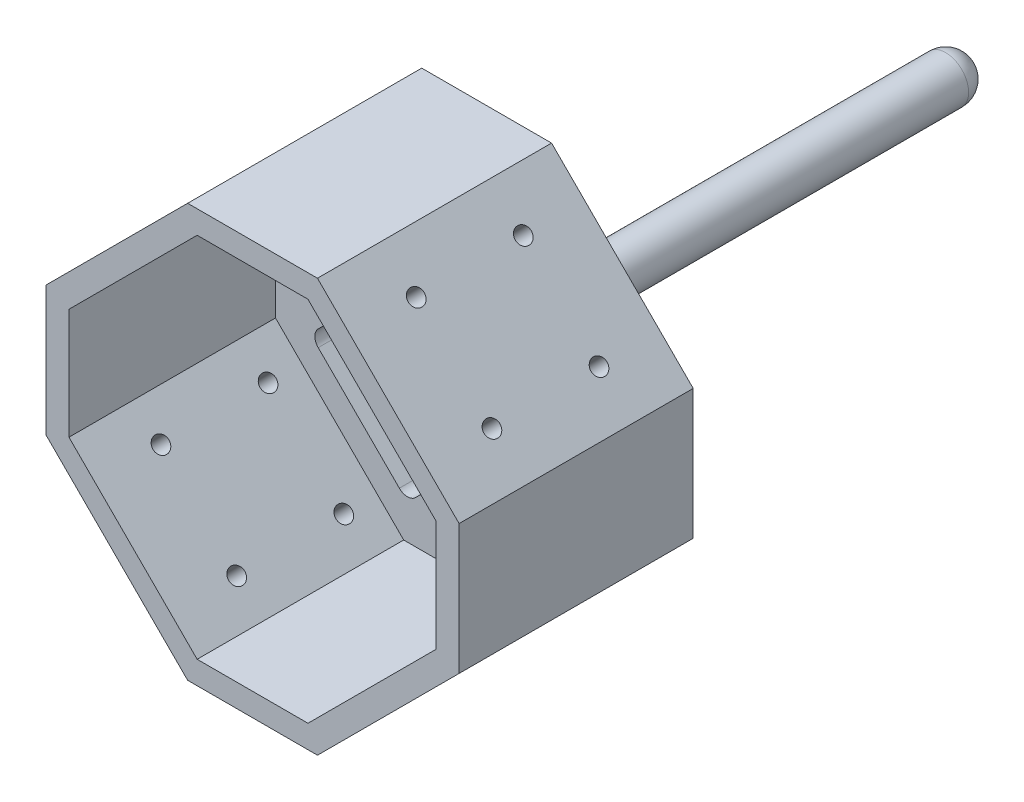
SolidWorks part; units mm, degrees
ref_plane "Plan de face" through (0, 0, 0) normal (0, 0, 1) x (1, 0, 0)
ref_plane "Plan de dessus" through (0, 0, 0) normal (0, 1, 0) x (1, 0, 0)
ref_plane "Plan de droite" through (0, 0, 0) normal (1, 0, 0) x (0, 0, -1)
sketch "Esquisse4" plane through (0, 0, 0) normal (0, 0, 1) x (1, 0, 0)
  line L1 (-14.1421, 45) -> (14.1421, 45)
  line L2 (-45, 14.1421) -> (-45, -14.1421)
  line L3 (-14.1421, -45) -> (14.1421, -45)
  line L4 (45, 14.1421) -> (45, -14.1421)
  line L5 (-45, 14.1421) -> (-14.1421, 45)
  line L6 (14.1421, 45) -> (45, 14.1421)
  line L10 (45, -14.1421) -> (14.1421, -45)
  line L11 (-14.1421, -45) -> (-45, -14.1421)
  point P0 (0, 0)
  point P10 (-59.1421, 0)
  point P11 (0, 59.1421)
  point P12 (59.1421, 0)
  point P13 (0, -59.1421)
extrude "Boss.-Extru.2" add sketch "Esquisse4" along normal blind 50
sketch "Esquisse5" plane through (29.5711, 29.5711, 0) normal (0.7071, 0.7071, 0) x (0, 0, -1)
  circle A0 centre (-13.335, 11.665) radius 1.75
  circle A1 centre (-36.665, 11.665) radius 1.75
  circle A2 centre (-13.335, -11.665) radius 1.75
  circle A3 centre (-36.665, -11.665) radius 1.75
  point P5 (-25, 0)
  dimension "D3" = 3.5
  dimension "D1" = 23.33
  dimension "D2" = 23.33
extrude "Enlèv. mat.-Extru.2" cut sketch "Esquisse5" against normal through all
sketch "Esquisse6" plane through (29.5711, -29.5711, 0) normal (0.7071, -0.7071, 0) x (0, 0, -1)
  circle A0 centre (-13.335, 11.665) radius 1.75
  circle A1 centre (-36.665, 11.665) radius 1.75
  circle A2 centre (-13.335, -11.665) radius 1.75
  circle A3 centre (-36.665, -11.665) radius 1.75
  point P5 (-25, 0)
  dimension "D3" = 3.5
  dimension "D1" = 23.33
  dimension "D2" = 23.33
extrude "Enlèv. mat.-Extru.3" cut sketch "Esquisse6" against normal through all
sketch "Esquisse7" plane through (0, 0, 50) normal (0, 0, 1) x (1, 0, 0)
  line L0 (-45, 14.1421) -> (-14.1421, 45)
  line L1 (-14.1421, 45) -> (14.1421, 45)
  line L2 (14.1421, 45) -> (45, 14.1421)
  line L3 (45, 14.1421) -> (45, -14.1421)
  line L4 (45, -14.1421) -> (14.1421, -45)
  line L5 (14.1421, -45) -> (-14.1421, -45)
  line L6 (-14.1421, -45) -> (-45, -14.1421)
  line L7 (-45, -14.1421) -> (-45, 14.1421)
  line L8 (-40, 12.0711) -> (-12.0711, 40)
  line L9 (-12.0711, 40) -> (12.0711, 40)
  line L10 (12.0711, 40) -> (40, 12.0711)
  line L11 (40, 12.0711) -> (40, -12.0711)
  line L12 (40, -12.0711) -> (12.0711, -40)
  line L13 (12.0711, -40) -> (-12.0711, -40)
  line L14 (-12.0711, -40) -> (-40, -12.0711)
  line L15 (-40, -12.0711) -> (-40, 12.0711)
  dimension "D1" = 5
extrude "Enlèv. mat.-Extru.5" cut sketch "Esquisse7" against normal blind 44 contours L8 L9 L10 L11 L12 L13 L14 L15
sketch "Esquisse8" plane through (0, 0, 0) normal (0, 0, -1) x (-1, 0, 0)
  circle A0 centre (0, 0) radius 5
  dimension "D1" = 10
extrude "Boss.-Extru.3" add sketch "Esquisse8" along normal blind 100
sketch "Esquisse9" plane through (0, 0, 6) normal (0, 0, 1) x (1, 0, 0)
  line L4 (-13.0178, 13.0178) -> (-0.2898, 25.7457)
  line L5 (-0.2898, 25.7457) -> (-9.1287, 34.5845)
  line L9 (-25.7457, 0.2898) -> (-34.5845, 9.1287)
  line L10 (-34.5845, 9.1287) -> (-9.1287, 34.5845)
  line L11 (-25.7457, 0.2898) -> (-13.0178, 13.0178)
  line L12 (25.7457, -0.2898) -> (34.5845, -9.1287)
  line L13 (13.0178, -13.0178) -> (25.7457, -0.2898)
  line L14 (0.2898, -25.7457) -> (9.1287, -34.5845)
  line L15 (0.2898, -25.7457) -> (13.0178, -13.0178)
  line L16 (9.1287, -34.5845) -> (34.5845, -9.1287)
  line L17 (-13.0178, -13.0178) -> (-23.6244, -2.4112)
  line L18 (-23.6244, -2.4112) -> (-32.4632, -11.25)
  line L19 (-2.4112, -23.6244) -> (-11.25, -32.4632)
  line L20 (-11.25, -32.4632) -> (-32.4632, -11.25)
  line L21 (-2.4112, -23.6244) -> (-13.0178, -13.0178)
  line L22 (2.4112, 23.6244) -> (11.25, 32.4632)
  line L23 (32.4632, 11.25) -> (11.25, 32.4632)
  line L24 (23.6244, 2.4112) -> (32.4632, 11.25)
  line L25 (23.6244, 2.4112) -> (13.0178, 13.0178)
  line L26 (13.0178, 13.0178) -> (2.4112, 23.6244)
  dimension "D1" = 18
  dimension "D2" = 12.5
  dimension "D3" = 15
  dimension "D4" = 12.5
extrude "Enlèv. mat.-Extru.6" cut sketch "Esquisse9" against normal through all
fillet "Congé1" radius 2.5 16 edges at (-2.4112, -23.6244, 3) (-11.25, -32.4632, 3) (-23.6244, -2.4112, 3) (-32.4632, -11.25, 3) (-25.7457, 0.2898, 3) (-34.5845, 9.1287, 3) (-9.1287, 34.5845, 3) (-0.2898, 25.7457, 3) (2.4112, 23.6244, 3) (11.25, 32.4632, 3) (32.4632, 11.25, 3) (23.6244, 2.4112, 3) (25.7457, -0.2898, 3) (34.5845, -9.1287, 3) (0.2898, -25.7457, 3) (9.1287, -34.5845, 3)
sketch "Esquisse12" plane through (0, 0, -100) normal (0, 0, -1) x (-1, 0, 0)
  line L0 (-5, 0) -> (5, 0)
  arc A0 (5, 0) -> (-5, 0) centre (0, 0) ccw
revolve "Révolution1" add sketch "Esquisse12" angle 180 about L0
sketch "Esquisse13" plane through (0, 0, 50) normal (0, 0, 1) x (1, 0, 0)
  line L0 (-45, 14.1421) -> (-14.1421, 45)
  line L1 (-14.1421, 45) -> (14.1421, 45)
  line L2 (14.1421, 45) -> (45, 14.1421)
  line L3 (45, 14.1421) -> (45, -14.1421)
  line L4 (45, -14.1421) -> (14.1421, -45)
  line L5 (14.1421, -45) -> (-14.1421, -45)
  line L6 (-14.1421, -45) -> (-45, -14.1421)
  line L7 (-45, -14.1421) -> (-45, 14.1421)
  line L8 (-40, 12.0711) -> (-12.0711, 40)
  line L9 (-12.0711, 40) -> (12.0711, 40)
  line L10 (12.0711, 40) -> (40, 12.0711)
  line L11 (40, 12.0711) -> (40, -12.0711) construction
  line L12 (40, 12.0711) -> (40, -12.0711) construction
  line L13 (40, 12.0711) -> (40, -12.0711)
  line L14 (40, -12.0711) -> (12.0711, -40)
  line L15 (12.0711, -40) -> (-12.0711, -40)
  line L16 (-12.0711, -40) -> (-40, -12.0711)
  line L17 (-40, -12.0711) -> (-40, 12.0711)
extrude "Boss.-Extru.4" add sketch "Esquisse13" along normal blind 1
fillet "Congé2" radius 10 1 edges at (-5, 0, 0)
